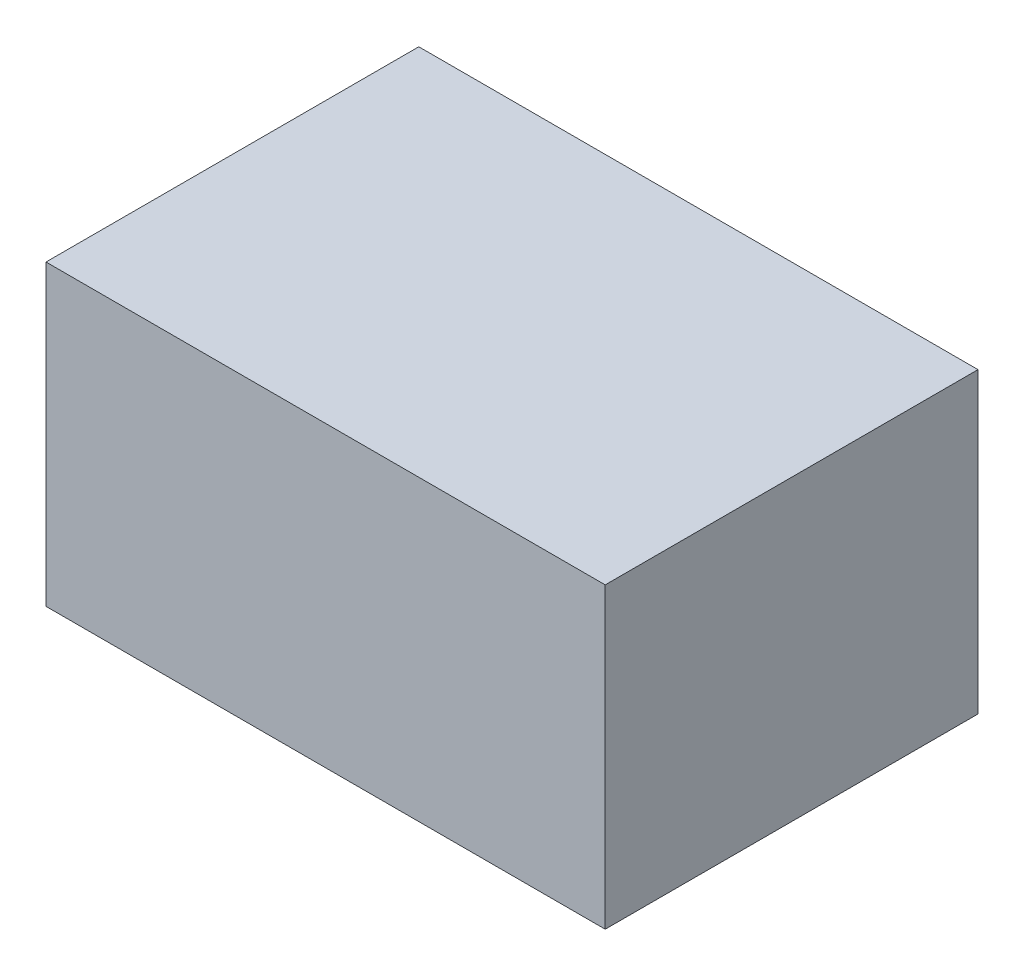
SolidWorks part; units mm, degrees
ref_plane "前视基准面" through (0, 0, 0) normal (0, 0, 1) x (1, 0, 0)
ref_plane "上视基准面" through (0, 0, 0) normal (0, 1, 0) x (1, 0, 0)
ref_plane "右视基准面" through (0, 0, 0) normal (1, 0, 0) x (0, 0, -1)
sketch "草图1" plane through (0, 0, 0) normal (0, 1, 0) x (1, 0, 0)
  line L1 (-75, 50) -> (75, 50)
  line L2 (-75, 50) -> (-75, -50)
  line L3 (-75, -50) -> (75, -50)
  line L4 (75, 50) -> (75, -50)
  dimension "D1" = 100
  dimension "D2" = 150
  dimension "D3" = 75
  dimension "D4" = 50
extrude "凸台-拉伸1" add sketch "草图1" along normal blind 80
